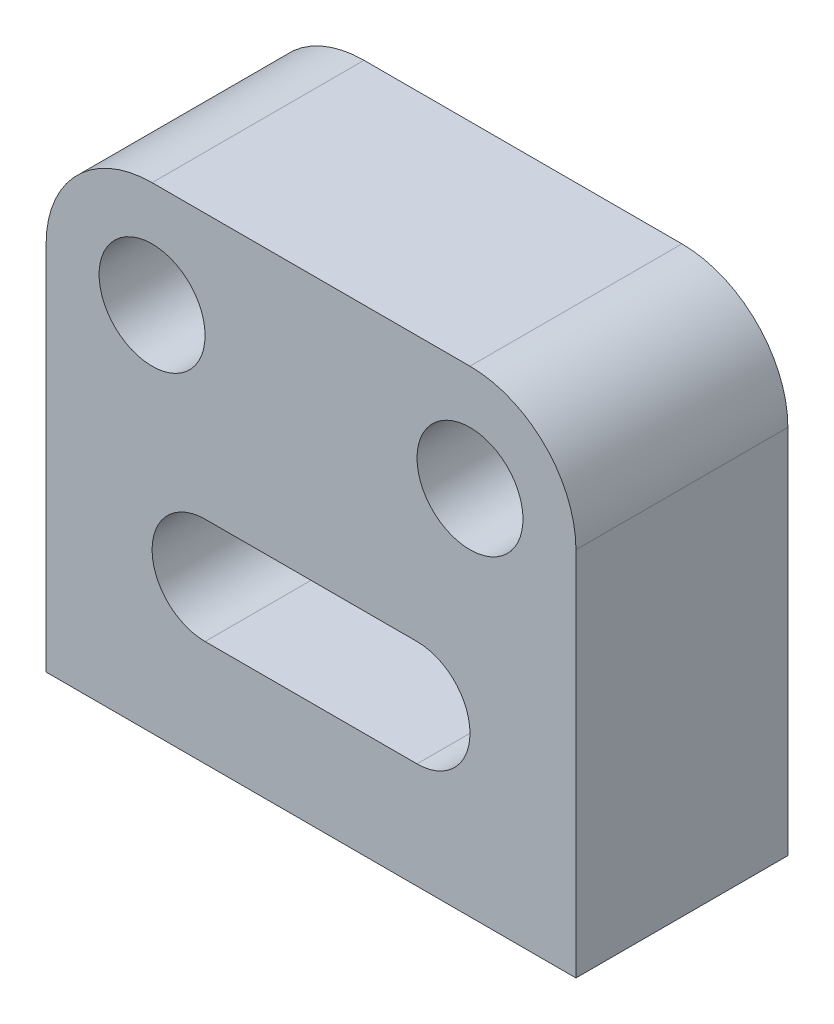
SolidWorks part; units mm, degrees
ref_plane "Front Plane" through (0, 0, 0) normal (0, 0, 1) x (1, 0, 0)
ref_plane "Top Plane" through (0, 0, 0) normal (0, 1, 0) x (1, 0, 0)
ref_plane "Right Plane" through (0, 0, 0) normal (1, 0, 0) x (0, 0, -1)
sketch "Sketch1" plane through (0, 0, 0) normal (0, 0, 1) x (1, 0, 0)
  line L0 (0, 0) -> (0, 55897.3099) construction
  line L1 (50, 0) -> (-50, 0)
  line L2 (-50, 0) -> (-50, 70)
  line L3 (-30, 90) -> (30, 90)
  line L4 (50, 0) -> (50, 70)
  line L5 (-20, 30) -> (20, 30) construction
  line L6 (-20, 40) -> (20, 40)
  line L7 (-20, 20) -> (20, 20)
  arc A0 (-50, 70) -> (-30, 90) centre (-30, 70) cw
  circle A1 centre (-30, 70) radius 10
  circle A2 centre (30, 70) radius 10
  arc A3 (50, 70) -> (30, 90) centre (30, 70) ccw
  arc A4 (-20, 40) -> (-20, 20) centre (-20, 30) ccw
  arc A5 (20, 20) -> (20, 40) centre (20, 30) ccw
  point P14 (0, 90)
  point P15 (0, 0)
  point P17 (0, 30)
  point P22 (0, 0)
  point P25 (23.363, 30)
  dimension "D4" = 20
  dimension "D1" = 90
  dimension "D2" = 20
  dimension "D3" = 50
  dimension "D5" = 20
  dimension "D6" = 30
  dimension "D7" = 40
extrude "Boss-Extrude1" add sketch "Sketch1" along normal blind 40
